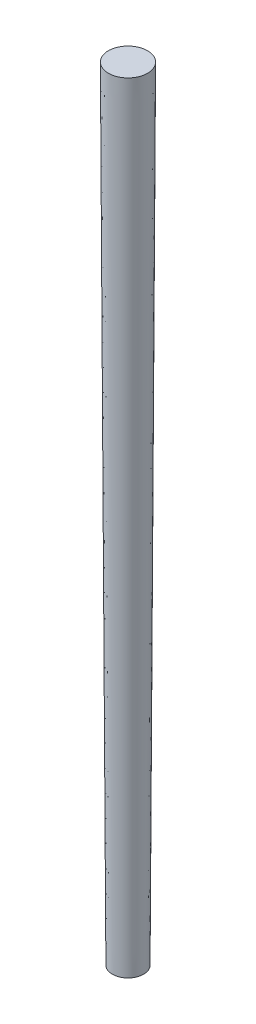
SolidWorks part; units mm, degrees
ref_plane "Front Plane" through (0, 0, 0) normal (0, 0, 1) x (1, 0, 0)
ref_plane "Top Plane" through (0, 0, 0) normal (0, 1, 0) x (1, 0, 0)
ref_plane "Right Plane" through (0, 0, 0) normal (1, 0, 0) x (0, 0, -1)
sketch "Sketch1" plane through (0, 0, 0) normal (0, 0, 1) x (1, 0, 0)
  line L0 (0, 63.5) -> (0, -63.5)
  line L1 (0, 63.5) -> (-3.175, 63.5)
  line L2 (-3.175, 63.5) -> (-2.54, -63.5)
  line L3 (-2.54, -63.5) -> (0, -63.5)
  dimension "D1" = 3.175
  dimension "D2" = 2.54
  dimension "D3" = 127
revolve "Revolve1" add sketch "Sketch1" angle 360 about L0
